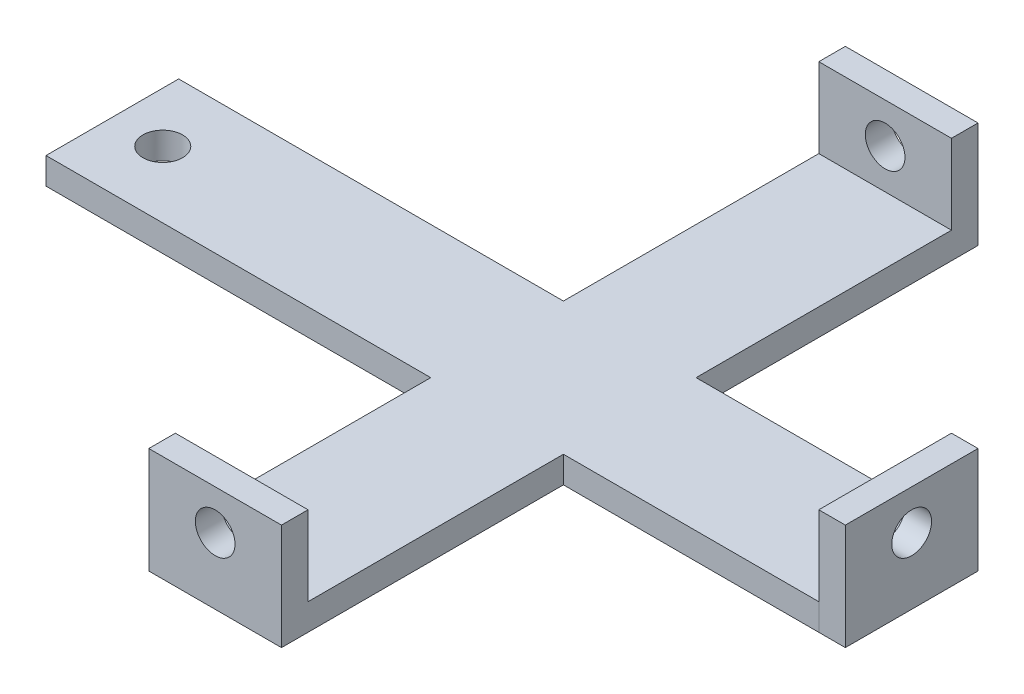
SolidWorks part; units mm, degrees
ref_plane "Front Plane" through (0, 0, 0) normal (0, 0, 1) x (1, 0, 0)
ref_plane "Top Plane" through (0, 0, 0) normal (0, 1, 0) x (1, 0, 0)
ref_plane "Right Plane" through (0, 0, 0) normal (1, 0, 0) x (0, 0, -1)
sketch "Sketch1" plane through (0, 0, 0) normal (1, 0, 0) x (0, 0, -1)
  line L0 (-1.27, 8.128) -> (60.325, 8.128)
  line L3 (60.325, 8.128) -> (60.325, 15.748)
  line L6 (-1.27, 8.128) -> (-1.27, 15.748)
  dimension "D2" = 61.595
  dimension "D3" = 7.62
extrude "Extrude-Thin1" add sketch "Sketch1" along normal blind 12.7 thin
hole_wizard "#6 Clearance Hole1" positions "Sketch3" profile "Sketch2" hole size "#6" standard "ANSI Inch"
sketch "Sketch3" plane through (0, 0, 1.27) normal (0, 0, -1) x (-1, 0, 0)
  line L0 (-12.7, 15.748) -> (0, 15.748) construction
  line L1 (0, 8.128) -> (0, 15.748) construction
  point P0 (-6.35, 11.938)
  dimension "D1" = 3.81
  dimension "D2" = 6.35
sketch "Sketch2" plane through (6.35, 11.938, 1.27) normal (1, 0, 0) x (0, 1, 0)
  line L0 (0, 0) -> (0, 8.7608)
  line L1 (0, 8.7608) -> (1.8986, 7.62)
  line L2 (1.8986, 7.62) -> (1.8986, 0)
  line L5 (1.8986, 0) -> (0, 0)
  line L10 (0, 8.7608) -> (-1.8986, 7.62) construction
  line L11 (0, -6.35) -> (0, 107.95) construction
  dimension "Hole Dia." = 3.7973
  dimension "Hole Depth" = 7.62
  dimension "Drill Angle" = 118
hole_wizard "#6 Clearance Hole2" positions "Sketch5" profile "Sketch4" hole size "#6" standard "ANSI Inch"
sketch "Sketch5" plane through (0, 0, -60.325) normal (0, 0, 1) x (1, 0, 0)
  line L0 (12.7, 15.748) -> (0, 15.748) construction
  line L1 (0, 15.748) -> (0, 8.128) construction
  point P0 (6.35, 11.938)
  dimension "D1" = 3.81
  dimension "D2" = 6.35
sketch "Sketch4" plane through (6.35, 11.938, -60.325) normal (1, 0, 0) x (0, -1, 0)
  line L0 (0, 0) -> (0, 8.7608)
  line L1 (0, 8.7608) -> (1.8986, 7.62)
  line L2 (1.8986, 7.62) -> (1.8986, 0)
  line L5 (1.8986, 0) -> (0, 0)
  line L10 (0, 8.7608) -> (-1.8986, 7.62) construction
  line L11 (0, -6.35) -> (0, 107.95) construction
  dimension "Hole Dia." = 3.7973
  dimension "Hole Depth" = 7.62
  dimension "Drill Angle" = 118
sketch "Sketch6" plane through (12.7, 0, 0) normal (1, 0, 0) x (0, 0, -1)
  line L0 (60.325, 8.128) -> (-1.27, 8.128) construction
  line L1 (23.1775, 8.128) -> (35.8775, 8.128)
  line L2 (23.1775, 8.128) -> (23.1775, 5.588)
  line L3 (23.1775, 5.588) -> (35.8775, 5.588)
  line L4 (35.8775, 8.128) -> (35.8775, 5.588)
  line L5 (62.865, 5.588) -> (-3.81, 5.588) construction
  line L7 (60.325, 15.748) -> (60.325, 8.128) construction
  dimension "D1" = 12.7
  dimension "D2" = 24.4475
extrude "Boss-Extrude1" add sketch "Sketch6" along normal blind 24.4475
sketch "Sketch7" plane through (37.1475, 0, 0) normal (1, 0, 0) x (0, 0, -1)
  line L5 (23.1775, 5.588) -> (35.8775, 5.588)
  line L6 (23.1775, 5.588) -> (23.1775, 15.748)
  line L7 (23.1775, 15.748) -> (35.8775, 15.748)
  line L8 (35.8775, 5.588) -> (35.8775, 15.748)
  dimension "D1" = 10.16
  dimension "D2" = 12.7
extrude "Boss-Extrude2" add sketch "Sketch7" along normal blind 2.54 separate body contours L7 L8 L5 L6
sketch "Sketch9" plane through (39.6875, 0, 0) normal (1, 0, 0) x (0, 0, -1)
  line L0 (35.8775, 5.588) -> (35.8775, 15.748) construction
  line L1 (23.1775, 15.748) -> (35.8775, 15.748) construction
  circle A0 centre (29.5275, 11.938) radius 1.905
  dimension "D1" = 3.81
  dimension "D2" = 6.35
  dimension "D3" = 3.81
extrude "Cut-Extrude1" cut sketch "Sketch9" against normal blind 2.54
sketch "Sketch10" plane through (0, 0, 0) normal (-1, 0, 0) x (0, 0, 1)
  line L0 (-60.325, 8.128) -> (1.27, 8.128) construction
  line L1 (-35.8775, 8.128) -> (-23.1775, 8.128)
  line L2 (-35.8775, 8.128) -> (-35.8775, 5.588)
  line L3 (-35.8775, 5.588) -> (-23.1775, 5.588)
  line L4 (-23.1775, 8.128) -> (-23.1775, 5.588)
  line L5 (-62.865, 5.588) -> (3.81, 5.588) construction
  line L8 (1.27, 8.128) -> (1.27, 15.748) construction
  dimension "D1" = 12.7
  dimension "D2" = 24.4475
extrude "Boss-Extrude3" add sketch "Sketch10" along normal blind 36.83
hole_wizard "#6 Clearance Hole3" positions "Sketch13" profile "Sketch12" hole size "#6" standard "ANSI Inch" end condition up to next
sketch "Sketch13" plane through (0, 8.128, 0) normal (0, 1, 0) x (1, 0, 0)
  line L0 (-36.83, 23.1775) -> (0, 23.1775) construction
  line L2 (0, 62.865) -> (0, 35.8775) construction
  point P1 (-32.004, 29.5275)
  dimension "D1" = 6.35
  dimension "D2" = 32.004
sketch "Sketch12" plane through (-32.004, 8.128, -29.5275) normal (1, 0, 0) x (0, 0, 1)
  line L0 (0, 0) -> (0, 2.541)
  line L1 (0, 2.541) -> (1.8986, 2.541)
  line L2 (1.8986, 2.541) -> (1.8986, 0)
  line L5 (1.8986, 0) -> (0, 0)
  line L11 (0, -6.35) -> (0, 107.95) construction
  dimension "Thru Hole Dia." = 3.7973
  dimension "Thru Hole Depth" = 2.5411
